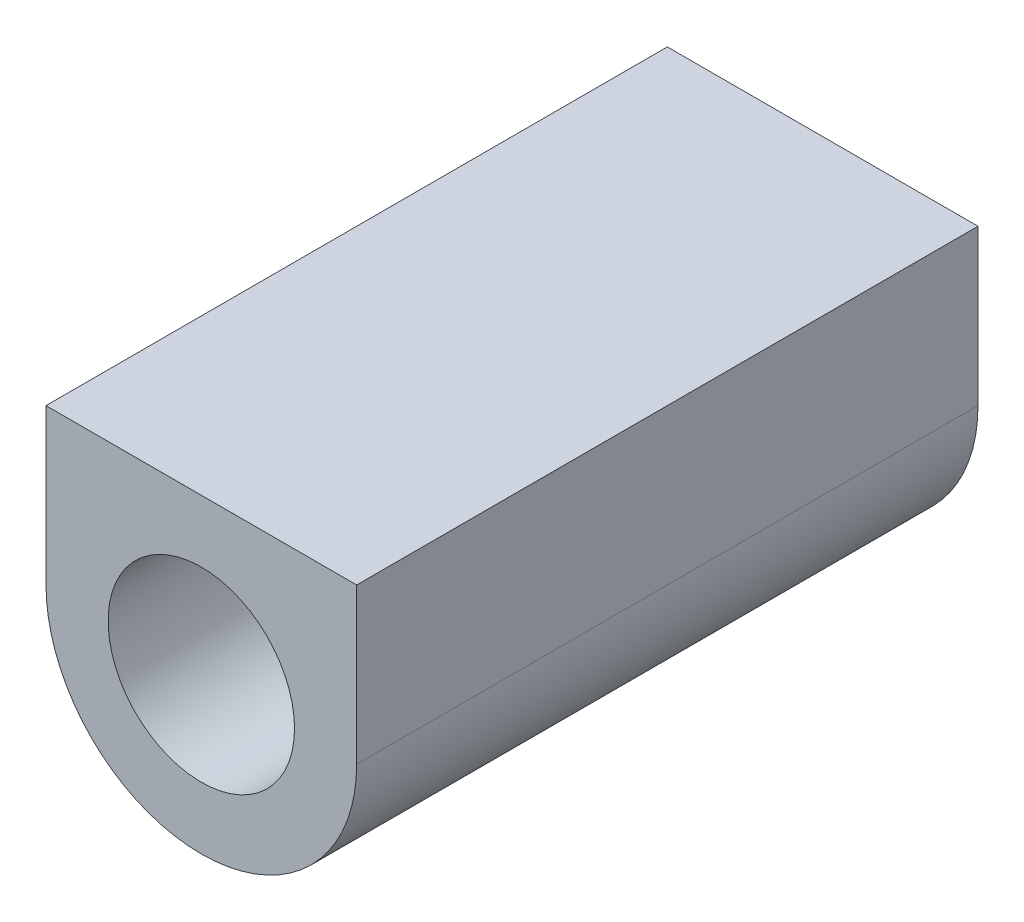
SolidWorks part; units mm, degrees
material "ABS"
ref_plane "Plan de face" through (0, 0, 0) normal (0, 0, 1) x (1, 0, 0)
ref_plane "Plan de dessus" through (0, 0, 0) normal (0, 1, 0) x (1, 0, 0)
ref_plane "Plan de droite" through (0, 0, 0) normal (1, 0, 0) x (0, 0, -1)
sketch "Esquisse1" plane through (0, 0, 0) normal (0, 0, 1) x (1, 0, 0)
  line L1 (0, 0) -> (5, 0)
  line L2 (0, 0) -> (0, 5)
  line L3 (0, 5) -> (5, 5)
  line L4 (5, 0) -> (5, 5)
  dimension "D1" = 5
extrude "Boss.-Extru.1" add sketch "Esquisse1" along normal blind 10
sketch "Esquisse2" plane through (0, 0, 10) normal (0, 0, 1) x (1, 0, 0)
  line L0 (0, 5) -> (0, 0) construction
  line L1 (5, 0) -> (5, 5) construction
  line L2 (0, 2.5) -> (0, 0)
  line L3 (0, 0) -> (2.5, 0)
  line L4 (2.5, 0) -> (5, 0)
  line L5 (5, 0) -> (5, 2.5)
  arc A0 (0, 2.5) -> (5, 2.5) centre (2.5, 2.5) ccw
  circle A1 centre (2.5, 2.5) radius 1.5
  line M1 (0, 5) -> (0, 0)
  line M2 (0, 0) -> (5, 0)
  line M3 (5, 0) -> (5, 5)
  dimension "D1" = 3
extrude "Enlèv. mat.-Extru.1" cut sketch "Esquisse2" against normal through all contours A1 | A0 M2 M3 | A0 M1 M2
